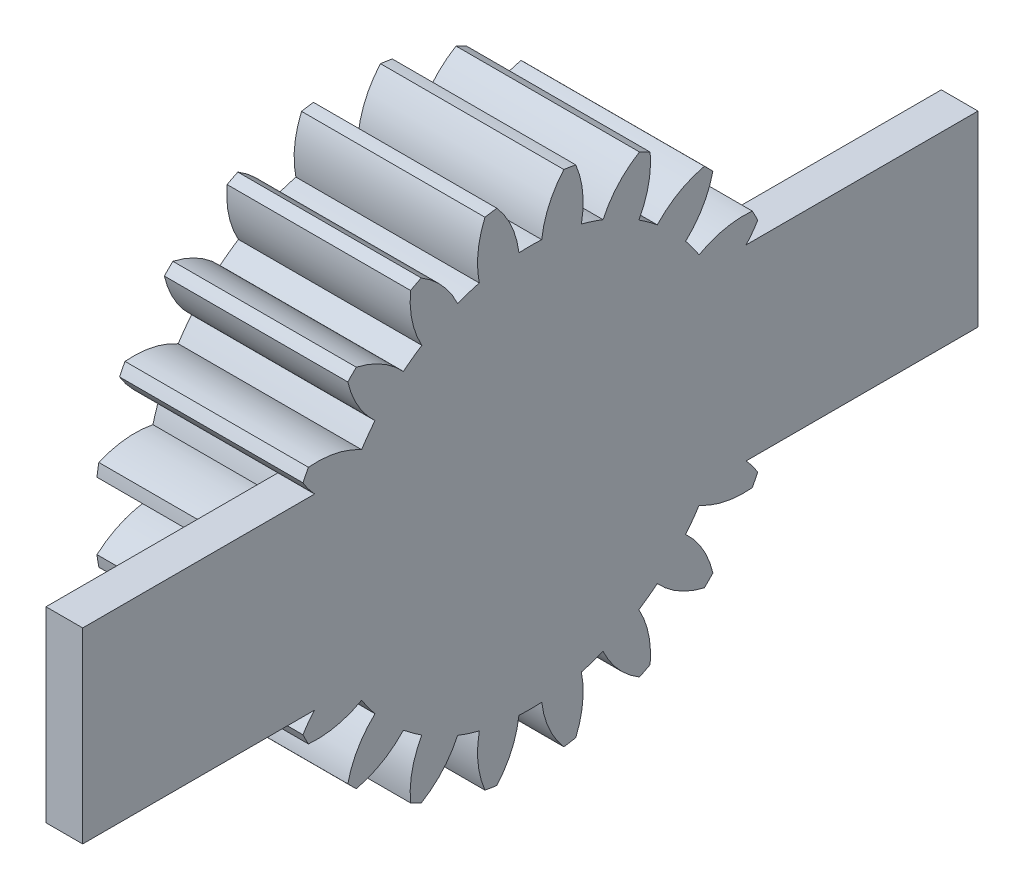
SolidWorks part; units mm, degrees
ref_plane "Plane1" through (0, 0, 0) normal (0, 0, 1) x (1, 0, 0)
ref_plane "Plane2" through (0, 0, 0) normal (0, 1, 0) x (1, 0, 0)
ref_plane "Plane3" through (0, 0, 0) normal (1, 0, 0) x (0, 0, -1)
sketch "HoldingSke" plane through (0, 0, 0) normal (0, 1, 0) x (1, 0, 0)
  line L0 (0, 0) -> (381.8911, -138.997)
  line L1 (-15, 0) -> (100, 0) construction
  line L2 (0, 0) -> (-2.1039, 2.3779)
  line L3 (0, 0) -> (-11.863, 4.5341)
  line L4 (0, 0) -> (8.1152, 2.9537)
  line L5 (0, 0) -> (-47.5972, -17.7524)
  line L6 (0, 0) -> (-10.5278, -7.1032)
  line L7 (-2.1039, 2.3779) -> (8.8308, 51.9871)
  line L8 (-76.2, 54.61) -> (-71.1708, 54.61)
  line L9 (-71.009, 38.7566) -> (-53.1078, 45.2721)
  line L10 (-76.2, 71.12) -> (104.1128, 71.12)
  line L11 (0, 0) -> (-12.7, 0)
  line L12 (-76.2, 101.6) -> (-76.1428, 101.6)
  line L13 (24.9733, 27.94) -> (52.9518, 28.4284)
  line L14 (24.9733, 27.94) -> (24.9746, 27.94)
  line L15 (24.9733, 27.94) -> (100.4006, 29.5858)
  circle A0 centre (0, 0) radius 2.3813
  circle A1 centre (0, 0) radius 13.8894
  circle A2 centre (0, 0) radius 38.1
  circle A3 centre (0, 0) radius 2.3813
  dimension "MHD" = 27.7787
  dimension "Hub_dia" = 76.2
  dimension "Bore" = 4.7625
  dimension "MBD" = 4.7625
  dimension "Num_teeth" = 20
  dimension "Pitch_radius" = 180.3128
  dimension "Pitch" = 406.4
  dimension "Width" = 12.7
  dimension "Overall_len" = 50.8
  dimension "Show_teeth" = 20
  dimension "Thickness" = 12.7
  dimension "OAL" = 50.8001
  dimension "T_dim" = 5.0292
  dimension "Ap" = 20
  dimension "H" = 19.05
  dimension "Backlash" = 0.0571
  dimension "Addendum_fac" = 1
  dimension "Dedendum_fac" = 1.25
  dimension "Clearance_fac" = 0.25
  dimension "Dedendum_add" = 0.0013
sketch "BasProSke" plane through (0, 0, 0) normal (0, 1, 0) x (1, 0, 0)
  line L0 (-10, 0) -> (60, 0) construction
  line L1 (0, 0) -> (0, 17.4625)
  line L2 (0, 0) -> (12.7, 0)
  line L3 (12.7, 0) -> (12.7, 17.4625)
  line L4 (12.7, 17.4625) -> (0, 17.4625)
  dimension "Diameter" = 34.925
  dimension "Thickness" = 12.7
revolve "Base-Revolve" add sketch "BasProSke" angle 360 about L0
sketch "TooCutSke" plane through (0, 0, 0) normal (1, 0, 0) x (0, 0, -1)
  line L1 (0, 0) -> (0, 107) construction
  line L2 (0, 0) -> (-1.3455, 15.8179) construction
  line L3 (0, 0) -> (-4.9538, 31.2774) construction
  line L4 (-1.3455, 15.8179) -> (-2.4769, 15.6387) construction
  arc A0 (0.7888, 13.8669) -> (-0.7888, 13.8669) centre (0, 0) ccw
  arc A1 (2.3397, 17.3307) -> (-2.3397, 17.3307) centre (0, 0) ccw
  circle A2 centre (0, 0) radius 15.875 construction
  circle A3 centre (0, 0) radius 14.9176 construction
  arc A4 (-0.7888, 13.8669) -> (-2.3397, 17.3307) centre (-7.095, 13.1224) ccw
  arc A5 (2.3397, 17.3307) -> (0.7888, 13.8669) centre (7.095, 13.1224) ccw
  dimension "Root_dia" = 27.7787
  dimension "Overcut_dia" = 34.9758
  dimension "Pitch_dia" = 31.75
  dimension "Base_dia" = 29.8352
  dimension "Flank_rad" = 6.35
  dimension "Half_ang" = 9
  dimension "Half_CT" = 1.1455
extrude "ToothCut" cut sketch "TooCutSke" along normal through all
fillet "Breaks" [suppressed] radius 0.0318
fillet "RootFillets" [suppressed] radius 0.3981
pattern_circular "TeethCuts" count 20 every 18 about axis through (-10, 0, 0) along (1, 0, 0) of "ToothCut", "RootFillets", "Breaks"
sketch "HubNeaOneSke" plane through (0, 0, 0) normal (-1, 0, 0) x (0, 0, 1)
  circle A0 centre (0, 0) radius 13.8894
  dimension "Diameter" = 27.7787
extrude "HubNearOne" [suppressed] add sketch "HubNeaOneSke" along normal blind 38.1001
sketch "HubNeaBotSke" plane through (0, 0, 0) normal (-1, 0, 0) x (0, 0, 1)
  circle A0 centre (0, 0) radius 13.8894
  dimension "Diameter" = 27.7787
extrude "HubNearBoth" [suppressed] add sketch "HubNeaBotSke" along normal blind 19.05
ref_plane "FarPln" through (12.7, 0, 0) normal (1, 0, 0) x (0, 0, -1)
sketch "HubFarSke" plane through (12.7, 0, 0) normal (1, 0, 0) x (0, 0, -1)
  circle A0 centre (0, 0) radius 13.8894
  dimension "Diameter" = 27.7787
extrude "HubFar" [suppressed] add sketch "HubFarSke" along normal blind 19.05
sketch "BorSke" plane through (0, 0, 0) normal (1, 0, 0) x (0, 0, -1)
  circle A0 centre (0, 0) radius 2.3813
  dimension "Diameter" = 4.7625
extrude "Bore" cut sketch "BorSke" along normal mid plane 101.6001
sketch "KeySke" plane through (0, 0, 0) normal (1, 0, 0) x (0, 0, -1)
  line L0 (-0.127, 0) -> (-0.127, 2.6479)
  line L1 (-0.127, 2.6479) -> (0.127, 2.6479)
  line L2 (0.127, 2.6479) -> (0.127, 0)
  line L3 (0, 0) -> (0, 34) construction
  line L4 (-0.127, 0) -> (0.127, 0)
  dimension "Offset" = 2.6479
  dimension "Width" = 0.254
extrude "Keyway" [suppressed] cut sketch "KeySke" along normal mid plane 101.6001
pattern_circular "Keyway2" [suppressed] count 2 every 90 about axis through (-10, 0, 0) along (1, 0, 0)
sketch "Sketch1" plane through (12.7, 0, 0) normal (1, 0, 0) x (0, 0, -1)
  line L0 (-30.996, -6.4778) -> (-30.996, 6.4778)
  line L1 (-30.996, -6.4778) -> (30.996, -6.4778)
  line L2 (-30.996, 6.4778) -> (30.996, 6.4778)
  line L3 (30.996, -6.4778) -> (30.996, 6.4778)
  line L4 (-30.996, -6.4778) -> (30.996, 6.4778) construction
  line L5 (-30.996, 6.4778) -> (30.996, -6.4778) construction
  point P1 (0, 0)
extrude "Boss-Extrude1" add sketch "Sketch1" against normal blind 2.54
equation "' \"Pitch@HoldingSke\" = 4"
equation "' \"Num_teeth@HoldingSke\" = 12"
equation "' \"Ap@HoldingSke\" =  20"
equation "' \"Width@HoldingSke\" = 0.5"
equation "' \"Hub_dia@HoldingSke\"= 1"
equation "' \"Overall_len@HoldingSke\" = 1.0"
equation "' \"Bore@HoldingSke\" = 0.75"
equation "' \"T_dim@HoldingSke\" = 0.85"
equation "' \"Width@KeySke\" = 0.25"
equation "' \"Show_teeth@HoldingSke\" = 13"
equation "' \"Backlash@HoldingSke\" = 0.009"
equation "' \"Addendum_fac@HoldingSke\" = 1.0"
equation "' \"Dedendum_fac@HoldingSke\" = 1.25"
equation "' \"Dedendum_add@HoldingSke\" = 0.00005"
equation "' \"Clearance_fac@HoldingSke\" = 0.25"
equation "' \"Pitch@HoldingSke\" = 0.5"
equation "' \"Num_teeth@HoldingSke\" = 23"
equation "' \"Show_teeth@HoldingSke\" = 23"
equation "' \"Backlash@HoldingSke\" = 0.0375"
equation "\"Overcut_dia@TooCutSke\" = (\"Num_teeth@HoldingSke\" + 2 * \"Addendum_fac@HoldingSke\") / \"Pitch@HoldingSke\" + 0.002"
equation "\"Pitch_dia@TooCutSke\" = \"Num_teeth@HoldingSke\" / \"Pitch@HoldingSke\""
equation "\"Base_dia@TooCutSke\" = \"Num_teeth@HoldingSke\" / \"Pitch@HoldingSke\" * cos((\"Ap@HoldingSke\"  * 3.14159265 / 180))"
equation "\"Root_dia@TooCutSke\" = (\"Num_teeth@HoldingSke\" + 2) / \"Pitch@HoldingSke\" - 2 * (\"Addendum_fac@HoldingSke\" + \"Dedendum_fac@HoldingSke\") / \"Pitch@HoldingSke\" - \"Dedendum_add@HoldingSke\" * 2"
equation "\"Half_ang@TooCutSke\" = 180 / \"Num_teeth@HoldingSke\""
equation "\"Half_CT@TooCutSke\" = \"Num_teeth@HoldingSke\" / \"Pitch@HoldingSke\" * sin((3.14159265 / 2 / \"Num_teeth@HoldingSke\")) / 2 - 7 * \"Backlash@HoldingSke\" / 4"
equation "\"Flank_rad@TooCutSke\" = \"Num_teeth@HoldingSke\" / \"Pitch@HoldingSke\" / 5"
equation "\"Radius@RootFillets\" = \"Clearance_fac@HoldingSke\" / \"Pitch@HoldingSke\" + \"Dedendum_add@HoldingSke\""
equation "\"Break_rad@Breaks\" = 0.02 / \"Pitch@HoldingSke\""
equation "\"Thickness@HoldingSke\" = \"Width@HoldingSke\""
equation "\"OAL@HoldingSke\" = \"Thickness@HoldingSke\""
equation "\"MHD@HoldingSke\" = (\"Num_teeth@HoldingSke\" + 2) / \"Pitch@HoldingSke\" - 2 * (\"Addendum_fac@HoldingSke\" + \"Dedendum_fac@HoldingSke\")  / \"Pitch@HoldingSke\" - \"Dedendum_add@HoldingSke\" * 2"
equation "\"MBD@HoldingSke\" = (\"Num_teeth@HoldingSke\" + 2) / \"Pitch@HoldingSke\" - 2 * (\"Addendum_fac@HoldingSke\" + \"Dedendum_fac@HoldingSke\")  / \"Pitch@HoldingSke\" - \"Dedendum_add@HoldingSke\" * 2 - 0.002"
equation "\"MHD@HoldingSke\" = ((sgn( \"MHD@HoldingSke\" - \"Hub_dia@HoldingSke\" )-1)*( \"MHD@HoldingSke\" - \"Hub_dia@HoldingSke\" ))/-2+ \"Hub_dia@HoldingSke\""
equation "\"MBD@HoldingSke\" = ((sgn( \"MBD@HoldingSke\" - \"Bore@HoldingSke\" )-1)*( \"MBD@HoldingSke\" - \"Bore@HoldingSke\" ))/-2+ \"Bore@HoldingSke\""
equation "\"OAL@HoldingSke\" = ((sgn( \"OAL@HoldingSke\" - \"Overall_len@HoldingSke\" )+1)*( \"OAL@HoldingSke\" - \"Overall_len@HoldingSke\" ))/2 + \"Overall_len@HoldingSke\" + 0.000002"
equation "\"Num_teeth@TeethCuts\" = int( \"Show_teeth@HoldingSke\" ) + 1"
equation "\"Num_teeth@TeethCuts\" = ((sgn( \"Num_teeth@TeethCuts\" - \"Num_teeth@HoldingSke\" )-1)*( \"Num_teeth@TeethCuts\" - \"Num_teeth@HoldingSke\" ))/-2+ \"Num_teeth@HoldingSke\""
equation "\"Num_teeth@TeethCuts\" = ((sgn( \"Num_teeth@TeethCuts\" - 2.0)+1)*( \"Num_teeth@TeethCuts\" - 2.0))/2 +2.0"
equation "\"Angle@TeethCuts\" = 360.0 / \"Num_teeth@HoldingSke\""
equation "\"Diameter@BasProSke\" = (\"Num_teeth@HoldingSke\" + 2 * \"Addendum_fac@HoldingSke\") / \"Pitch@HoldingSke\""
equation "\"Thickness@BasProSke\"  = \"Thickness@HoldingSke\""
equation "' \"Fillet_rad@BasProSke\" =  \"Thickness@HoldingSke\" * 0.05"
equation "\"MHD@HoldingSke\" = ((sgn( \"MHD@HoldingSke\" - \"Root_dia@TooCutSke\" )-1)*( \"MHD@HoldingSke\" - \"Root_dia@TooCutSke\" ))/-2+ \"Root_dia@TooCutSke\""
equation "\"Diameter@HubNeaOneSke\" = \"MHD@HoldingSke\""
equation "\"Length@HubNearOne\" = \"OAL@HoldingSke\" - \"Thickness@BasProSke\""
equation "\"Diameter@HubNeaBotSke\" = \"MHD@HoldingSke\""
equation "\"Length@HubNearBoth\" = ( \"OAL@HoldingSke\" - \"Thickness@BasProSke\" ) / 2.0"
equation "\"Thickness@FarPln\" = \"Thickness@BasProSke\""
equation "\"Diameter@HubFarSke\" = \"MHD@HoldingSke\""
equation "\"Length@HubFar\" = ( \"OAL@HoldingSke\" - \"Thickness@BasProSke\" ) / 2.0"
equation "\"Diameter@BorSke\" = \"MBD@HoldingSke\""
equation "\"D1@Bore\" = \"OAL@HoldingSke\" * 2.0"
equation "\"D1@Keyway\" = \"OAL@HoldingSke\" * 2.0"
equation "\"Offset@KeySke\" = \"T_dim@HoldingSke\" - \"MBD@HoldingSke\" / 2.0"
